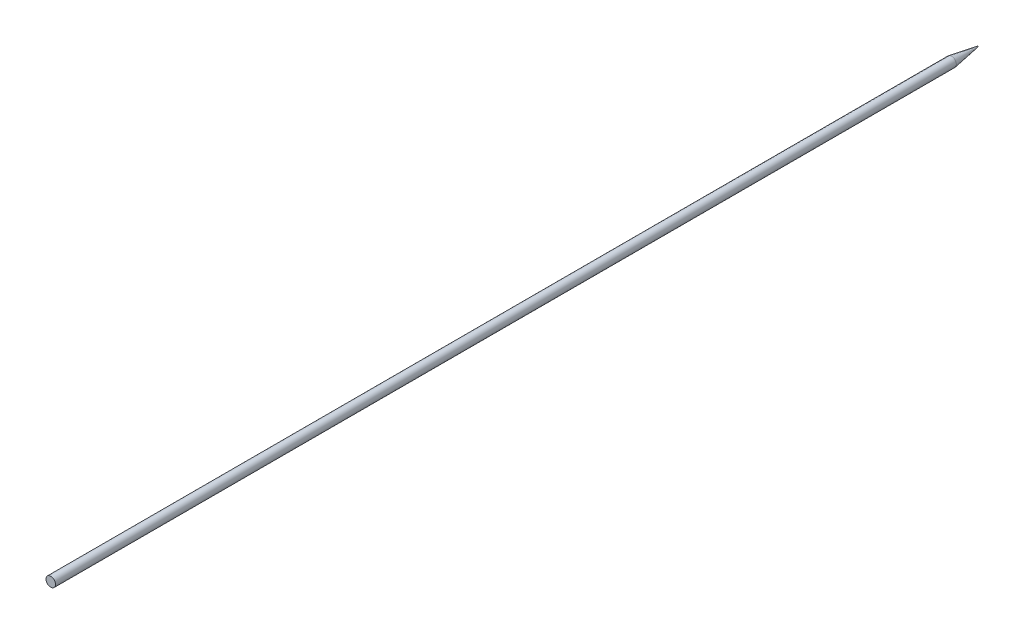
SolidWorks part; units mm, degrees
material "AISI Type 316L stainless steel"
ref_plane "Front Plane" through (0, 0, 0) normal (0, 0, 1) x (1, 0, 0)
ref_plane "Top Plane" through (0, 0, 0) normal (0, 1, 0) x (1, 0, 0)
ref_plane "Right Plane" through (0, 0, 0) normal (1, 0, 0) x (0, 0, -1)
sketch "Sketch1" plane through (0, 0, 0) normal (0, 1, 0) x (1, 0, 0)
  line L1 (0, 0) -> (0, 5.5296)
  line L3 (0, 0) -> (0, -189.4704)
  line L4 (0, -189.4704) -> (1, -189.4704)
  line L5 (1, -189.4704) -> (1, 0)
  line L6 (1, 0) -> (0.0933, 5.4402)
  spline S0 degree 2 poles (0, 5.5296) (0.0722, 5.5265) (0.0933, 5.4402) knots 0 0 0 1 1 1
  dimension "D1" = 1
  dimension "D2" = 195
revolve "Revolve1" add sketch "Sketch1" angle 360 about L1
